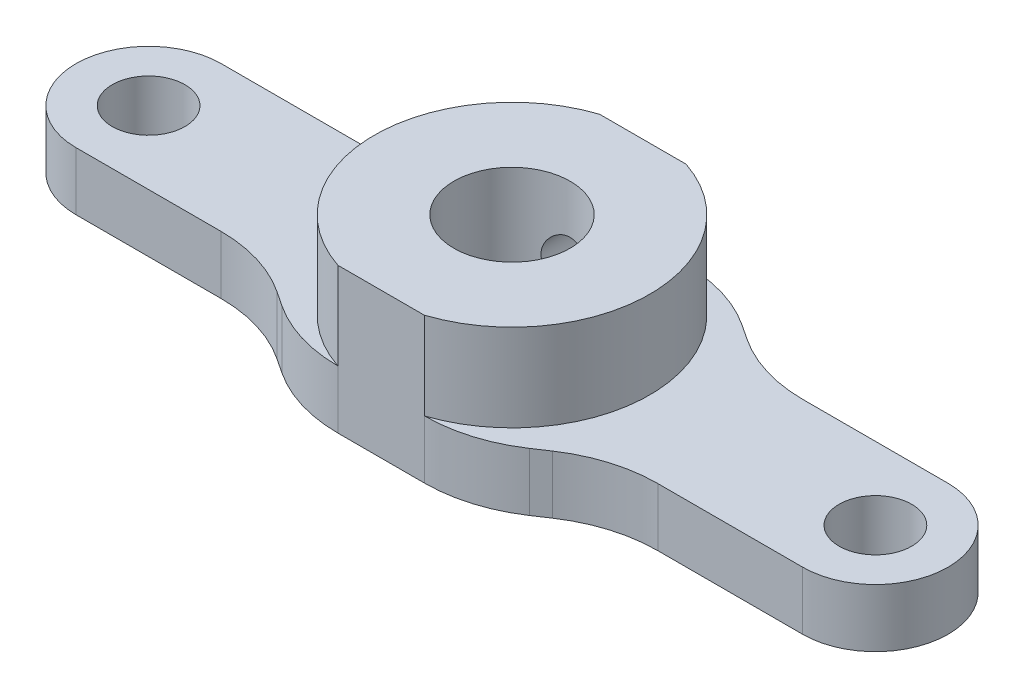
SolidWorks part; units mm, degrees
material "Plain Carbon Steel"
ref_plane "Front Plane" through (0, 0, 0) normal (0, 0, 1) x (1, 0, 0)
ref_plane "Top Plane" through (0, 0, 0) normal (0, 1, 0) x (1, 0, 0)
ref_plane "Right Plane" through (0, 0, 0) normal (1, 0, 0) x (0, 0, -1)
sketch "Sketch1" plane through (0, 0, 0) normal (0, 1, 0) x (1, 0, 0)
  line L0 (0, 0) -> (-50, 0) construction
  line L1 (0, -5) -> (-50, -5)
  line L2 (0, 5) -> (-50, 5)
  line L3 (-25, 5) -> (-25, -5) construction
  line L4 (5, 0) -> (-55, 0) construction
  line L5 (-25, 5) -> (-25, 9)
  line L6 (-27.9722, 9) -> (-22.0278, 9)
  line L7 (-16.4808, 7.3205) -> (-15.5192, 6.6795)
  line L8 (-9.9722, 5) -> (0, 5)
  line L9 (-33.5192, 7.3205) -> (-34.4808, 6.6795)
  line L10 (5, 0) -> (-55, 0) construction
  line L11 (-21, 0) -> (-29, 0)
  line L12 (5, 0) -> (-55, 0)
  line L13 (-33.5192, -7.3205) -> (-34.4808, -6.6795)
  line L14 (-16.4808, -7.3205) -> (-15.5192, -6.6795)
  line L15 (-27.9722, -9) -> (-22.0278, -9)
  arc A0 (0, -5) -> (0, 5) centre (0, 0) ccw
  arc A1 (-50, 5) -> (-50, -5) centre (-50, 0) ccw
  circle A2 centre (-50, 0) radius 2.5
  circle A4 centre (0, 0) radius 2.5
  circle A5 centre (-25, 0) radius 4
  arc A6 (-22.0278, 9) -> (-16.4808, 7.3205) centre (-22.0278, -1) cw
  arc A7 (-15.5192, 6.6795) -> (-9.9722, 5) centre (-9.9722, 15) ccw
  arc A8 (-34.4808, 6.6795) -> (-40.0278, 5) centre (-40.0278, 15) cw
  arc A9 (-27.9722, 9) -> (-33.5192, 7.3205) centre (-27.9722, -1) ccw
  arc A10 (-27.9722, -9) -> (-33.5192, -7.3205) centre (-27.9722, 1) cw
  arc A11 (-34.4808, -6.6795) -> (-40.0278, -5) centre (-40.0278, -15) ccw
  arc A12 (-15.5192, -6.6795) -> (-9.9722, -5) centre (-9.9722, -15) cw
  arc A13 (-22.0278, -9) -> (-16.4808, -7.3205) centre (-22.0278, 1) ccw
  point P3 (-25, 0)
  point P24 (-19, 9)
  point P27 (-13, 5)
  point P34 (-37, 5)
  point P35 (-31, 9)
  point P51 (-31, -9)
  point P52 (-37, -5)
  point P53 (-13, -5)
  point P54 (-19, -9)
  dimension "D2" = 5
  dimension "D3" = 5
  dimension "D4" = 8
  dimension "D5" = 4
  dimension "D9" = 15.0278
  dimension "D8" = 10
  dimension "D1" = 50
  dimension "D6" = 6
  dimension "D7" = 6
extrude "Boss-Extrude1" add sketch "Sketch1" along normal blind 4 contours A5 L12 A2 A1 L1 A0 A4 | A5 L12 A4 A0 L2 A1 A2 | L15 A13 L14 A12 L1 A11 L13 A10 | A7 L7 A6 L6 L5 L2 | L6 A9 L9 A8 L2 L5
sketch "Sketch4" plane through (0, 4, 0) normal (0, 1, 0) x (1, 0, 0)
  line L0 (-22.0278, 9) -> (-27.9722, 9)
  line L1 (-22.0278, -9) -> (-27.9722, -9)
  circle A0 centre (-25, 0) radius 4
  circle A1 centre (-25, 0) radius 9.4781
  line M3 (-22.0278, 9) -> (-27.9722, 9)
  line M13 (-27.9722, -9) -> (-22.0278, -9)
  circle M25 centre (-25, 0) radius 4
  dimension "D1" = 8
extrude "Boss-Extrude3" add sketch "Sketch4" along normal blind 6 contours A1 M13 M3 M25
sketch "Sketch5" plane through (0, 0, -9) normal (0, 0, -1) x (-1, 0, 0)
  line L0 (22.0278, 10) -> (27.9722, 10) construction
  line L2 (25, 10) -> (25, 0)
  line L3 (27.9722, 0) -> (22.0278, 0) construction
  circle A0 centre (25, 5) radius 1.65
  dimension "D1" = 3.3
  dimension "D2" = 5
  dimension "D3" = 0
extrude "Cut-Extrude1" cut sketch "Sketch5" against normal blind 6 contours L2 A0 | L2 A0
